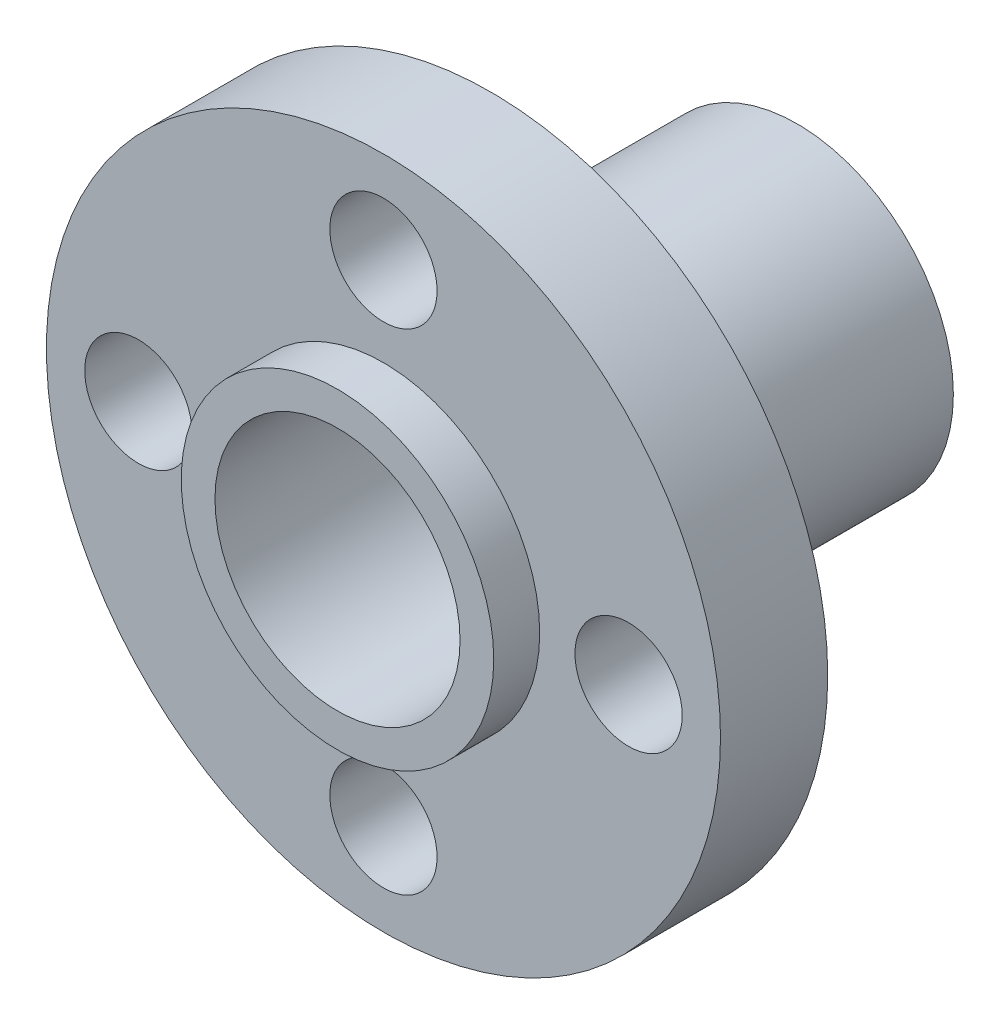
SolidWorks part; units mm, degrees
material "Brass"
ref_plane "Front Plane" through (0, 0, 0) normal (0, 0, 1) x (1, 0, 0)
ref_plane "Top Plane" through (0, 0, 0) normal (0, 1, 0) x (1, 0, 0)
ref_plane "Right Plane" through (0, 0, 0) normal (1, 0, 0) x (0, 0, -1)
sketch "Sketch1" plane through (0, 0, 0) normal (0, 0, 1) x (1, 0, 0)
  circle A0 centre (0, 0) radius 11
  circle A1 centre (0, 0) radius 5.1
  circle A2 centre (0, 0) radius 8 construction
  circle A3 centre (0, 8) radius 1.75
  circle A4 centre (8, 0) radius 1.75
  circle A5 centre (0, -8) radius 1.75
  circle A6 centre (-8, 0) radius 1.75
  point P16 (0, 0)
  dimension "D1" = 22
  dimension "D2" = 10.2
  dimension "D3" = 16
  dimension "D4" = 3.5
  dimension "D5" = 4
extrude "Boss-Extrude1" add sketch "Sketch1" against normal blind 3.5
sketch "Sketch2" plane through (0, 0, 0) normal (0, 0, 1) x (1, 0, 0)
  circle A0 centre (0, 0) radius 5.1
  circle A1 centre (0, 0) radius 4
  dimension "D1" = 8
extrude "Boss-Extrude2" add sketch "Sketch2" along normal blind 1.5 and the other way blind 13.5
sketch "Sketch3" plane through (0, 0, 1.5) normal (0, 0, 1) x (1, 0, 0)
  circle A0 centre (0, 0) radius 4
curve "Helix/Spiral1" pitch 2 height 15 turns 7.5
sketch "Sketch4" plane through (0, 0, 0) normal (0, 1, 0) x (1, 0, 0)
  line L0 (3, -0.55) -> (3, -2.45)
  line L1 (3, -2.45) -> (5, -1.7146)
  line L2 (5, -1.7146) -> (5, -1.2854)
  line L3 (5, -1.2854) -> (3, -0.55)
  line L4 (3, -1.5) -> (5, -1.5)
  point P6 (4, -1.5)
  dimension "D1" = 1.9
  dimension "D2" = 2
  dimension "D3" = 69.811
